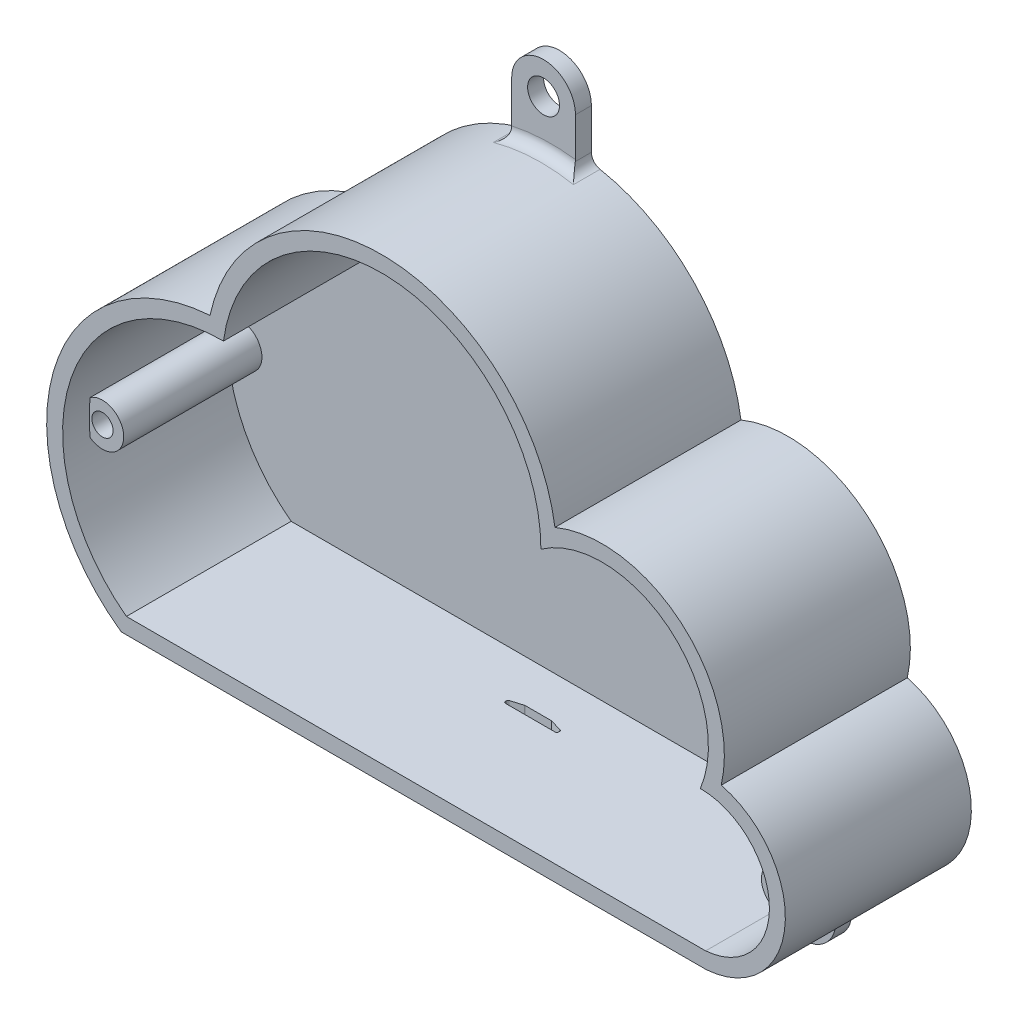
SolidWorks part; units mm, degrees
ref_plane "Plan de face" through (0, 0, 0) normal (0, 0, 1) x (1, 0, 0)
ref_plane "Plan de dessus" through (0, 0, 0) normal (0, 1, 0) x (1, 0, 0)
ref_plane "Plan de droite" through (0, 0, 0) normal (1, 0, 0) x (0, 0, -1)
sketch "Esquisse1" plane through (0, 0, 0) normal (0, 0, 1) x (1, 0, 0)
  line L3 (54.5, 0) -> (-54.5, 0)
  arc A0 (54.5, 0) -> (53.4984, 25.9614) centre (53.4984, 12.9614) ccw
  arc A2 (53.4984, 25.9614) -> (23.4984, 49.9614) centre (35.0203, 33.6137) ccw
  arc A4 (23.4984, 49.9614) -> (-36.2337, 54) centre (-6.5016, 50) ccw
  arc A5 (-36.2337, 54) -> (-54.5, 0) centre (-36.5016, 24.0012) ccw
  dimension "D3" = 30
  dimension "D4" = 20
  dimension "D5" = 13
  dimension "D2" = 30
  dimension "D1" = 50
  dimension "D6" = 90
  dimension "D7" = 37
  dimension "D8" = 109
  dimension "D9" = 54
  dimension "D10" = 60
  dimension "D11" = 30
extrude "Boss.-Extru.1" add sketch "Esquisse1" along normal blind 4
sketch "Esquisse4" plane through (0, 0, 0) normal (0, 0, 1) x (1, 0, 0)
  line L1 (-54.5, 0) -> (54.5, 0)
  line L2 (-54.5, 0) -> (54.5, 0)
  line L5 (-55.4736, -3) -> (54.6097, -3)
  line L6 (-55.4736, -3) -> (54.6097, -3)
  arc A4 (53.4984, 25.9614) -> (23.4984, 49.9614) centre (35.0203, 33.6137) ccw
  arc A5 (23.4984, 49.9614) -> (-36.2337, 54) centre (-6.5016, 50) ccw
  arc A6 (-36.2337, 54) -> (-54.5, 0) centre (-36.5016, 24.0012) ccw
  arc A7 (54.5, 0) -> (53.4984, 25.9614) centre (53.4984, 12.9614) ccw
  arc A8 (53.4984, 25.9614) -> (23.4984, 49.9614) centre (35.0203, 33.6137) ccw
  arc A9 (23.4984, 49.9614) -> (-36.2337, 54) centre (-6.5016, 50) ccw
  arc A10 (-36.2337, 54) -> (-54.5, 0) centre (-36.5016, 24.0012) ccw
  arc A11 (54.5, 0) -> (53.4984, 25.9614) centre (53.4984, 12.9614) ccw
  arc A20 (57.4375, 28.4689) -> (26.1428, 54.8314) centre (35.0203, 33.6137) ccw
  arc A21 (26.1428, 54.8314) -> (-38.7671, 56.9233) centre (-6.5016, 50) ccw
  arc A22 (-38.7671, 56.9233) -> (-55.4736, -3) centre (-36.5016, 24.0012) ccw
  arc A23 (54.6097, -3) -> (57.4375, 28.4689) centre (53.4984, 12.9614) ccw
  arc A24 (57.4375, 28.4689) -> (26.1428, 54.8314) centre (35.0203, 33.6137) ccw
  arc A25 (26.1428, 54.8314) -> (-38.7671, 56.9233) centre (-6.5016, 50) ccw
  arc A26 (-38.7671, 56.9233) -> (-55.4736, -3) centre (-36.5016, 24.0012) ccw
  arc A27 (54.6097, -3) -> (57.4375, 28.4689) centre (53.4984, 12.9614) ccw
  dimension "D1" = 0
  dimension "D2" = 3
extrude "Boss.-Extru.3" add sketch "Esquisse4" along normal blind 35
sketch "Esquisse5" plane through (0, 0, 0) normal (0, 0, 1) x (1, 0, 0)
  line L0 (-54.5, 0) -> (54.5, 0) construction
  line L1 (-87.6078, 26) -> (88.7895, 26) construction
  circle A0 centre (-42.2337, 50) radius 5
  circle A1 centre (-42.2337, 50) radius 1.5
  circle A2 centre (37.7663, 50) radius 5
  circle A3 centre (37.7663, 50) radius 1.5
  circle A4 centre (37.7663, 2) radius 1.5
  circle A5 centre (37.7663, 2) radius 5
  circle A6 centre (-42.2337, 2) radius 1.5
  circle A7 centre (-42.2337, 2) radius 5
  dimension "D1" = 10
  dimension "D2" = 3
  dimension "D3" = 6
  dimension "D4" = 50
  dimension "D6" = 26
  dimension "D5" = 2
extrude "Boss.-Extru.4" [suppressed] add sketch "Esquisse5" along normal blind 30
sketch "Esquisse2" plane through (0, 0, 0) normal (0, 0, 1) x (1, 0, 0)
  line L0 (0, -43.0758) -> (0, 91.7283) construction
  line L1 (-47, -3) -> (-47, -15)
  line L3 (-35, -15) -> (-35, -3)
  line L5 (35, -15) -> (35, -3)
  line L6 (47, -3) -> (47, -15)
  line L8 (-14, 82.1368) -> (-14, 92)
  line L15 (-2, 92) -> (-2, 82.6915)
  line L16 (-55.4736, -3) -> (54.6097, -3) construction
  line L17 (-47, -3) -> (-35, -3)
  line L18 (35, -3) -> (47, -3)
  arc A0 (-47, -15) -> (-35, -15) centre (-41, -15) ccw
  circle A1 centre (-41, -15) radius 3
  circle A2 centre (41, -15) radius 3
  arc A3 (47, -15) -> (35, -15) centre (41, -15) cw
  arc A10 (-14, 92) -> (-2, 92) centre (-8, 92) cw
  circle A11 centre (-8, 92) radius 3
  arc A12 (26.1428, 54.8314) -> (-38.7671, 56.9233) centre (-6.5016, 50) ccw construction
  arc A13 (-2, 82.6915) -> (-14, 82.1368) centre (-6.5016, 50) ccw
  dimension "D1" = 6
  dimension "D2" = 6
  dimension "D3" = 107
  dimension "D4" = 35
extrude "Boss.-Extru.2" add sketch "Esquisse2" along normal blind 3
sketch "Esquisse6" plane through (0, -3, 0) normal (0, -1, 0) x (1, 0, 0)
  line L4 (0, -6.8868) -> (0, 71.4533) construction
  line L5 (2.456, 12) -> (-2.456, 12)
  line L6 (-5, 13.2) -> (-5, 12.9732)
  line L7 (-4.7, 13.5) -> (4.7, 13.5)
  line L8 (-35, 0) -> (35, 0) construction
  line L9 (-4.7862, 12.6859) -> (-2.5422, 12.0127)
  line L10 (4.7862, 12.6859) -> (2.5422, 12.0127)
  line L11 (5, 13.2) -> (5, 12.9732)
  arc A0 (-2.456, 12) -> (-2.5422, 12.0127) centre (-2.456, 12.3) cw
  arc A1 (-5, 12.9732) -> (-4.7862, 12.6859) centre (-4.7, 12.9732) ccw
  arc A2 (-5, 13.2) -> (-4.7, 13.5) centre (-4.7, 13.2) cw
  arc A3 (5, 13.2) -> (4.7, 13.5) centre (4.7, 13.2) ccw
  arc A4 (5, 12.9732) -> (4.7862, 12.6859) centre (4.7, 12.9732) cw
  arc A5 (2.456, 12) -> (2.5422, 12.0127) centre (2.456, 12.3) ccw
  point P13 (0, 12)
  point P17 (-2.5, 12)
  point P20 (-5, 12.75)
  point P23 (-5, 13.5)
  point P25 (0, 12)
  point P32 (5, 13.5)
  point P33 (5, 12.75)
  point P35 (2.5, 12)
  point P36 (0, 13.5)
  dimension "D6" = 0.3
  dimension "D1" = 12
  dimension "D2" = 5
  dimension "D3" = 10
  dimension "D4" = 1.5
  dimension "D5" = 0.75
extrude "Enlèv. mat.-Extru.1" cut sketch "Esquisse6" against normal up to next
fillet "Congé1" radius 2 9 edges at (-2, 82.6915, 1.5) (-14, 82.1368, 1.5) (-8.0255, 82.9648, 3) (-47, -3, 1.5) (-35, -3, 1.5) (-41, -3, 3) (47, -3, 1.5) (35, -3, 1.5) (41, -3, 3)
sketch "Esquisse7" plane through (0, 0, 0) normal (0, 0, 1) x (1, 0, 0)
  line L0 (0, -20.4452) -> (0, 99.8082) construction
  circle A0 centre (0, 77.2347) radius 4
  circle A1 centre (64, 12) radius 2 construction
  arc A2 (26.1428, 54.8314) -> (-38.7671, 56.9233) centre (-6.5016, 50) ccw construction
  circle A3 centre (-64, 24) radius 2 construction
  circle A4 centre (0, 77.2347) radius 1.5
  circle A5 centre (64, 12) radius 2
  circle A6 centre (-64, 24) radius 2
  circle A7 centre (-64, 24) radius 4
  circle A8 centre (64, 12) radius 4
  dimension "D2" = 8
  dimension "D3" = 3
  dimension "D1" = 28
extrude "Boss.-Extru.5" add sketch "Esquisse7" along normal blind 30
